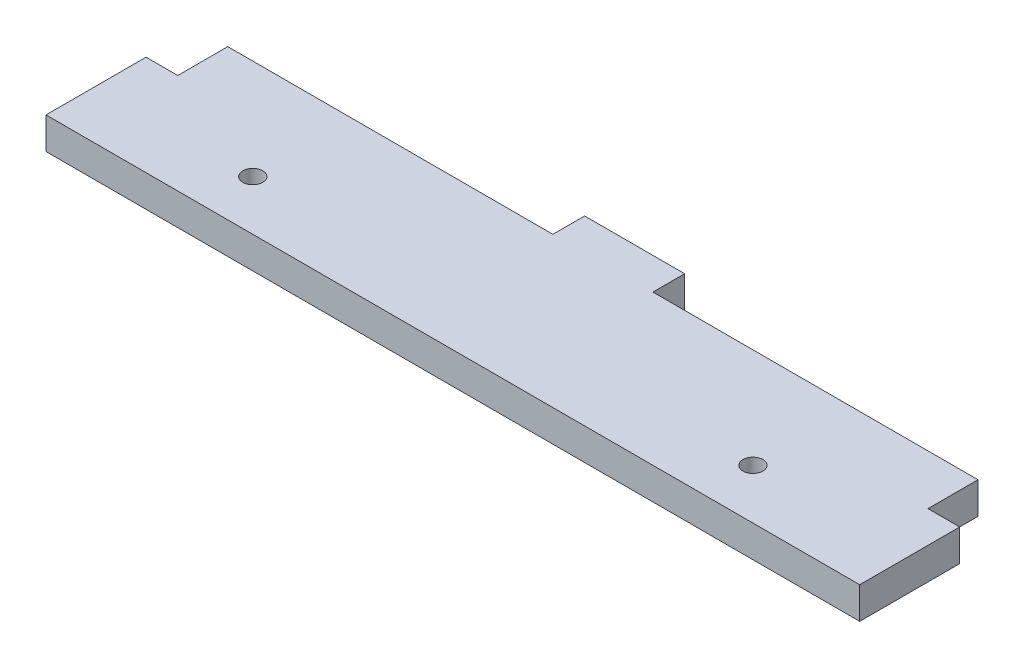
SolidWorks part; units mm, degrees
ref_plane "Front Plane" through (0, 0, 0) normal (0, 0, 1) x (1, 0, 0)
ref_plane "Top Plane" through (0, 0, 0) normal (0, 1, 0) x (1, 0, 0)
ref_plane "Right Plane" through (0, 0, 0) normal (1, 0, 0) x (0, 0, -1)
sketch "Sketch1" plane through (0, 0, 0) normal (0, 1, 0) x (1, 0, 0)
  line L0 (-81.35, -18.175) -> (81.35, -18.175)
  line L1 (81.35, -18.175) -> (81.35, 1.825)
  line L2 (81.35, 1.825) -> (75, 1.825)
  line L3 (75, 1.825) -> (75, 11.825)
  line L4 (75, 11.825) -> (10, 11.825)
  line L5 (10, 11.825) -> (10, 18.175)
  line L6 (10, 18.175) -> (-10, 18.175)
  line L7 (-10, 18.175) -> (-10, 11.825)
  line L8 (-10, 11.825) -> (-75, 11.825)
  line L9 (-75, 11.825) -> (-75, 1.825)
  line L10 (-75, 1.825) -> (-81.35, 1.825)
  line L11 (-81.35, 1.825) -> (-81.35, -18.175)
  line L12 (0, 18.175) -> (0, -18.175) construction
  line L13 (-50, -8.175) -> (50, -8.175) construction
  circle A0 centre (-50, -8.175) radius 2
  circle A1 centre (50, -8.175) radius 2
  point P20 (0, -8.175)
  dimension "D7" = 4
  dimension "D1" = 10
  dimension "D2" = 20
  dimension "D3" = 6.35
  dimension "D4" = 6.35
  dimension "D5" = 150
  dimension "D6" = 20
  dimension "D8" = 10
  dimension "D9" = 100
extrude "Boss-Extrude1" add sketch "Sketch1" along normal mid plane 6.35
